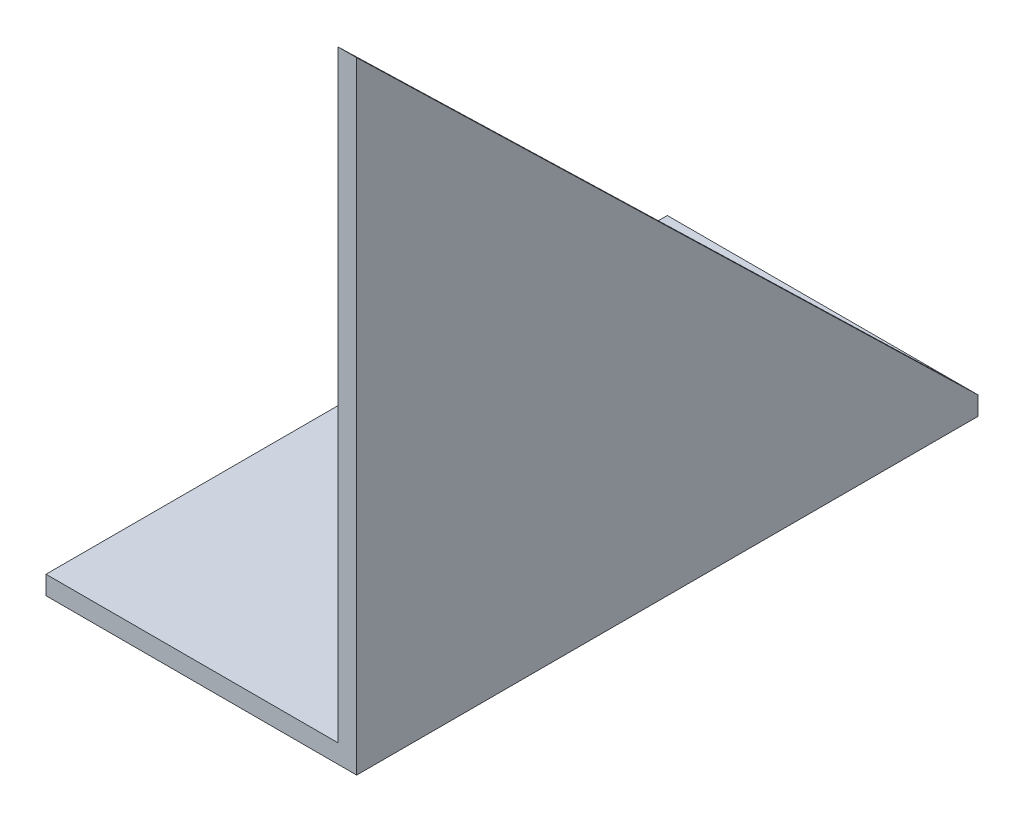
SolidWorks part; units mm, degrees
ref_plane "Alzado" through (0, 0, 0) normal (0, 0, 1) x (1, 0, 0)
ref_plane "Planta" through (0, 0, 0) normal (0, 1, 0) x (1, 0, 0)
ref_plane "Vista lateral" through (0, 0, 0) normal (1, 0, 0) x (0, 0, -1)
sketch "Croquis1" plane through (0, 0, 0) normal (0, 0, 1) x (1, 0, 0)
  line L1 (1.5, -50) -> (-1.5, -50)
  line L2 (1.5, -50) -> (1.5, 50)
  line L3 (1.5, 50) -> (-1.5, 50)
  line L4 (-1.5, -50) -> (-1.5, 50)
  line L5 (1.5, -50) -> (-1.5, 50) construction
  line L6 (1.5, 50) -> (-1.5, -50) construction
  line L7 (-1.5, -50) -> (-48.5, -50)
  line L8 (-1.5, -50) -> (-1.5, -47)
  line L9 (-1.5, -47) -> (-48.5, -47)
  line L10 (-48.5, -50) -> (-48.5, -47)
  point P0 (0, 0)
  dimension "D1" = 3
  dimension "D2" = 3
  dimension "D3" = 50
  dimension "D4" = 100
extrude "Saliente-Extruir1" add sketch "Croquis1" along normal mid plane 100 contours L4 L1 L2 L3 | L7 L10 L9 L8
sketch "Croquis3" plane through (-1.5, 0, 0) normal (-1, 0, 0) x (0, 0, 1)
  line L0 (50, 50) -> (-50, -47)
  line L4 (-50, -47) -> (50, -47)
  line L5 (50, -47) -> (50, 50)
  line L6 (50, 50) -> (-50, 50)
  line L7 (-50, 50) -> (-50, -47)
  line L8 (-50, -47) -> (50, -47)
  line L9 (50, -47) -> (50, 50)
  line L10 (50, 50) -> (-50, 50)
  line L11 (-50, 50) -> (-50, -47)
  line M7 (50, 50) -> (-50, 50)
  line M8 (-50, 50) -> (-50, -47)
  dimension "D1" = 0
extrude "Cortar-Extruir2" cut sketch "Croquis3" against normal blind 100 contours L0 M7 M8
